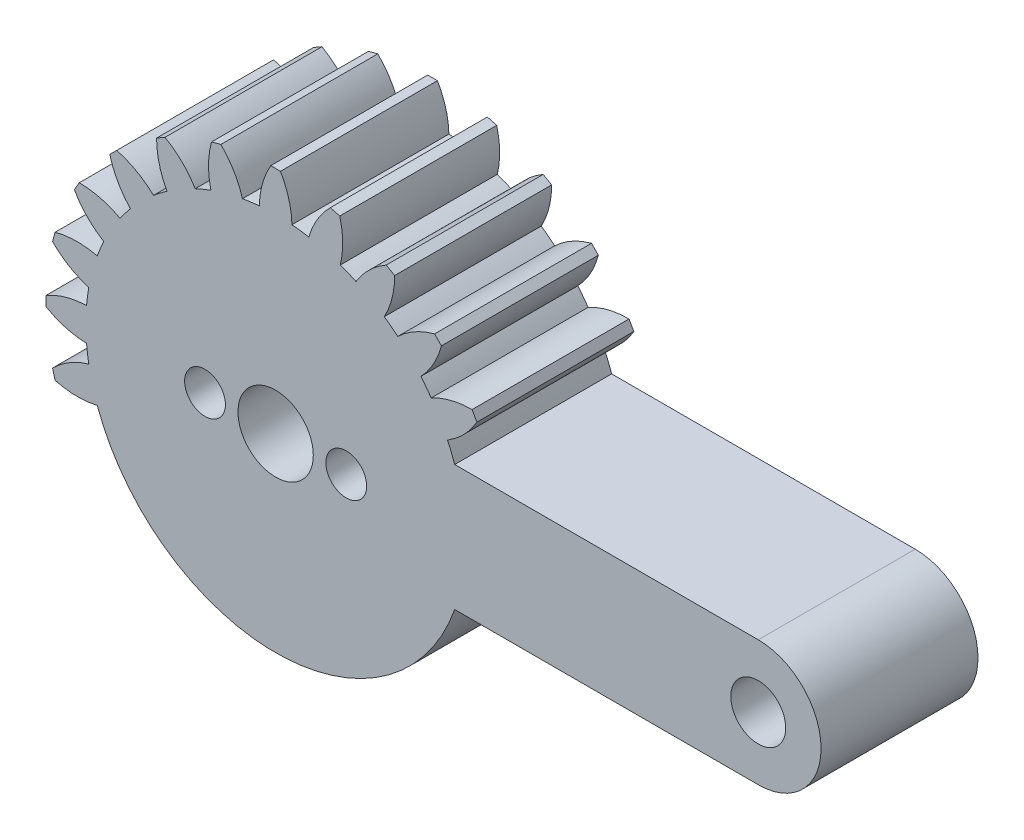
SolidWorks part; units mm, degrees
ref_plane "Front Plane" through (0, 0, 0) normal (0, 0, 1) x (1, 0, 0)
ref_plane "Top Plane" through (0, 0, 0) normal (0, 1, 0) x (1, 0, 0)
ref_plane "Right Plane" through (0, 0, 0) normal (1, 0, 0) x (0, 0, -1)
sketch "Sketch1" plane through (0, 0, 0) normal (0, 0, 1) x (1, 0, 0)
  line L0 (0, 0) -> (30.75, 0) construction
  line L1 (0, -14.63) -> (0, 14.63) construction
  line L2 (-0.31, 14.63) -> (0.31, 14.63)
  line L3 (3.4871, 14.2117) -> (4.086, 14.0513)
  line L4 (7.0465, 12.825) -> (7.5835, 12.515)
  line L5 (10.1258, 10.5642) -> (10.5642, 10.1258)
  line L6 (12.515, 7.5835) -> (12.825, 7.0465)
  line L7 (14.0513, 4.086) -> (14.2117, 3.4871)
  line L8 (14.63, 0.31) -> (14.63, -0.31)
  line L9 (14.2117, -3.4871) -> (14.0513, -4.086)
  line L10 (12.825, -7.0465) -> (12.515, -7.5835)
  line L11 (10.5642, -10.1258) -> (10.1258, -10.5642)
  line L12 (7.5835, -12.515) -> (7.0465, -12.825)
  line L13 (4.086, -14.0513) -> (3.4871, -14.2117)
  line L14 (0.31, -14.63) -> (-0.31, -14.63)
  line L15 (-3.4871, -14.2117) -> (-4.086, -14.0513)
  line L16 (-7.0465, -12.825) -> (-7.5835, -12.515)
  line L17 (-10.1258, -10.5642) -> (-10.5642, -10.1258)
  line L18 (-12.515, -7.5835) -> (-12.825, -7.0465)
  line L19 (-14.0513, -4.086) -> (-14.2117, -3.4871)
  line L20 (-14.63, -0.31) -> (-14.63, 0.31)
  line L21 (-14.2117, 3.4871) -> (-14.0513, 4.086)
  line L22 (-12.825, 7.0465) -> (-12.515, 7.5835)
  line L23 (-10.5642, 10.1258) -> (-10.1258, 10.5642)
  line L24 (-7.5835, 12.515) -> (-7.0465, 12.825)
  line L25 (-4.086, 14.0513) -> (-3.4871, 14.2117)
  line L26 (30.75, -4) -> (30.75, 4) construction
  line L27 (30.75, 4) -> (11.4091, 4)
  line L28 (30.75, -4) -> (11.4091, -4)
  circle A0 centre (0, 0) radius 1.75
  circle A1 centre (0, 0) radius 12.09
  circle A2 centre (30.75, 0) radius 1.75
  arc A3 (-1.04, 12.0452) -> (-0.31, 14.63) centre (4.3585, 11.9161) cw
  arc A4 (1.04, 12.0452) -> (0.31, 14.63) centre (-4.3585, 11.9161) ccw
  arc A5 (2.113, 11.9039) -> (3.4871, 14.2117) centre (7.294, 10.382) cw
  arc A6 (4.1221, 11.3656) -> (4.086, 14.0513) centre (-1.1258, 12.6381) ccw
  arc A7 (5.1219, 10.9514) -> (7.0465, 12.825) centre (9.7326, 8.1404) cw
  arc A8 (6.9233, 9.9114) -> (7.5835, 12.515) centre (2.1835, 12.4988) ccw
  arc A9 (7.7818, 9.2526) -> (10.1258, 10.5642) centre (11.5078, 5.344) cw
  arc A10 (9.2526, 7.7818) -> (10.5642, 10.1258) centre (5.344, 11.5078) ccw
  arc A11 (9.9114, 6.9233) -> (12.515, 7.5835) centre (12.4988, 2.1835) cw
  arc A12 (10.9514, 5.1219) -> (12.825, 7.0465) centre (8.1404, 9.7326) ccw
  arc A13 (11.3656, 4.1221) -> (14.0513, 4.086) centre (12.6381, -1.1258) cw
  arc A14 (11.9039, 2.113) -> (14.2117, 3.4871) centre (10.382, 7.294) ccw
  arc A15 (12.0452, 1.04) -> (14.63, 0.31) centre (11.9161, -4.3585) cw
  arc A16 (12.0452, -1.04) -> (14.63, -0.31) centre (11.9161, 4.3585) ccw
  arc A17 (11.9039, -2.113) -> (14.2117, -3.4871) centre (10.382, -7.294) cw
  arc A18 (11.3656, -4.1221) -> (14.0513, -4.086) centre (12.6381, 1.1258) ccw
  arc A19 (10.9514, -5.1219) -> (12.825, -7.0465) centre (8.1404, -9.7326) cw
  arc A20 (9.9114, -6.9233) -> (12.515, -7.5835) centre (12.4988, -2.1835) ccw
  arc A21 (9.2526, -7.7818) -> (10.5642, -10.1258) centre (5.344, -11.5078) cw
  arc A22 (7.7818, -9.2526) -> (10.1258, -10.5642) centre (11.5078, -5.344) ccw
  arc A23 (6.9233, -9.9114) -> (7.5835, -12.515) centre (2.1835, -12.4988) cw
  arc A24 (5.1219, -10.9514) -> (7.0465, -12.825) centre (9.7326, -8.1404) ccw
  arc A25 (4.1221, -11.3656) -> (4.086, -14.0513) centre (-1.1258, -12.6381) cw
  arc A26 (2.113, -11.9039) -> (3.4871, -14.2117) centre (7.294, -10.382) ccw
  arc A27 (1.04, -12.0452) -> (0.31, -14.63) centre (-4.3585, -11.9161) cw
  arc A28 (-1.04, -12.0452) -> (-0.31, -14.63) centre (4.3585, -11.9161) ccw
  arc A29 (-2.113, -11.9039) -> (-3.4871, -14.2117) centre (-7.294, -10.382) cw
  arc A30 (-4.1221, -11.3656) -> (-4.086, -14.0513) centre (1.1258, -12.6381) ccw
  arc A31 (-5.1219, -10.9514) -> (-7.0465, -12.825) centre (-9.7326, -8.1404) cw
  arc A32 (-6.9233, -9.9114) -> (-7.5835, -12.515) centre (-2.1835, -12.4988) ccw
  arc A33 (-7.7818, -9.2526) -> (-10.1258, -10.5642) centre (-11.5078, -5.344) cw
  arc A34 (-9.2526, -7.7818) -> (-10.5642, -10.1258) centre (-5.344, -11.5078) ccw
  arc A35 (-9.9114, -6.9233) -> (-12.515, -7.5835) centre (-12.4988, -2.1835) cw
  arc A36 (-10.9514, -5.1219) -> (-12.825, -7.0465) centre (-8.1404, -9.7326) ccw
  arc A37 (-11.3656, -4.1221) -> (-14.0513, -4.086) centre (-12.6381, 1.1258) cw
  arc A38 (-11.9039, -2.113) -> (-14.2117, -3.4871) centre (-10.382, -7.294) ccw
  arc A39 (-12.0452, -1.04) -> (-14.63, -0.31) centre (-11.9161, 4.3585) cw
  arc A40 (-12.0452, 1.04) -> (-14.63, 0.31) centre (-11.9161, -4.3585) ccw
  arc A41 (-11.9039, 2.113) -> (-14.2117, 3.4871) centre (-10.382, 7.294) cw
  arc A42 (-11.3656, 4.1221) -> (-14.0513, 4.086) centre (-12.6381, -1.1258) ccw
  arc A43 (-10.9514, 5.1219) -> (-12.825, 7.0465) centre (-8.1404, 9.7326) cw
  arc A44 (-9.9114, 6.9233) -> (-12.515, 7.5835) centre (-12.4988, 2.1835) ccw
  arc A45 (-9.2526, 7.7818) -> (-10.5642, 10.1258) centre (-5.344, 11.5078) cw
  arc A46 (-7.7818, 9.2526) -> (-10.1258, 10.5642) centre (-11.5078, 5.344) ccw
  arc A47 (-6.9233, 9.9114) -> (-7.5835, 12.515) centre (-2.1835, 12.4988) cw
  arc A48 (-5.1219, 10.9514) -> (-7.0465, 12.825) centre (-9.7326, 8.1404) ccw
  arc A49 (-4.1221, 11.3656) -> (-4.086, 14.0513) centre (1.1258, 12.6381) cw
  arc A50 (-2.113, 11.9039) -> (-3.4871, 14.2117) centre (-7.294, 10.382) ccw
  arc A51 (30.75, -4) -> (30.75, 4) centre (30.75, 0) ccw
  point P8 (0, 0)
  point P157 (30.75, 0)
  dimension "D2" = 3.5
  dimension "D3" = 3.5
  dimension "D4" = 24.18
  dimension "D6" = 5.4
  dimension "D10" = 8
  dimension "D1" = 30.75
  dimension "D5" = 29.26
  dimension "D7" = 0.31
  dimension "D8" = 1.04
  dimension "D9" = 24
extrude "Boss-Extrude4" add sketch "Sketch1" along normal blind 10 contours A1 | L28 A51 L27 L7 A14 A1 A15 L8 A16 A17 L9 A2 | A1 A38 L19 A37 | A1 A40 L20 A39 | A1 A42 L21 A41 | A1 A44 L22 A43 | A1 A46 L23 A45 | A1 A48 L24 A47 | A1 A50 L25 A49 | A1 A4 L2 A3 | A1 A6 L3 A5 | A1 A8 L4 A7 | A1 A10 L5 A9 | A1 A12 L6 A11 | A1 A14 L7 L27 | A1 A16 L8 A15 | A17 A1 L28 L9
sketch "Sketch2" plane through (0, 0, 10) normal (0, 0, 1) x (1, 0, 0)
  line L0 (-4.5, 0) -> (4.5, 0) construction
  circle A0 centre (-4.5, 0) radius 1.3
  circle A1 centre (4.5, 0) radius 1.3
  circle A2 centre (0, 0) radius 2.4
  point P5 (0, 0)
  dimension "D2" = 2.6
  dimension "D3" = 2.6
  dimension "D4" = 4.8
  dimension "D1" = 9
extrude "Cut-Extrude1" cut sketch "Sketch2" against normal through all
